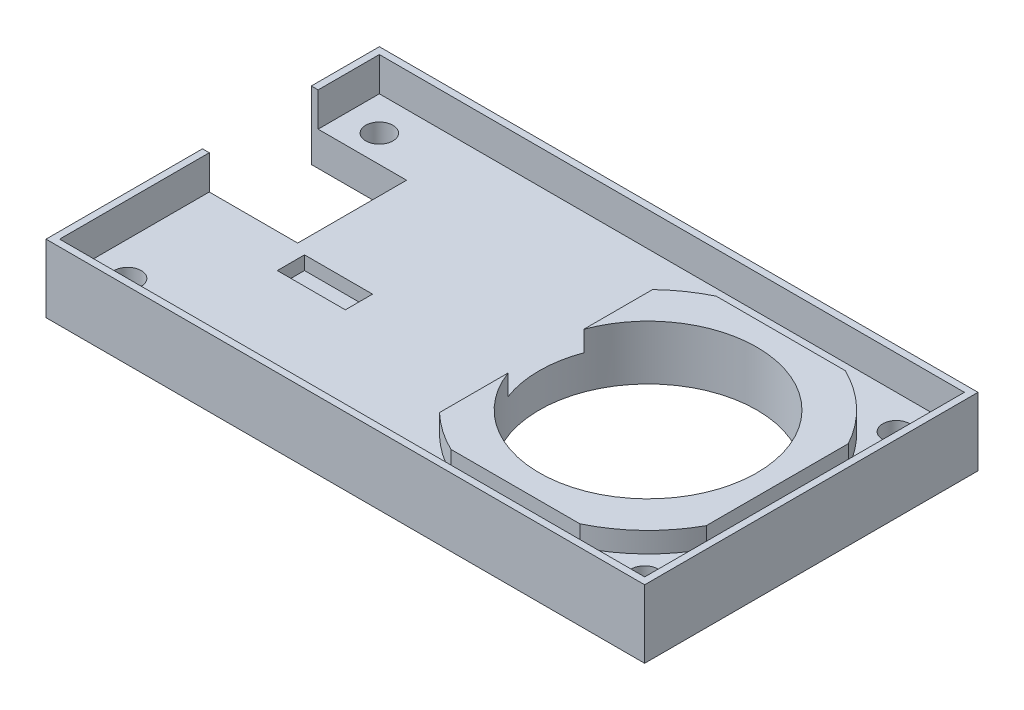
SolidWorks part; units mm, degrees
ref_plane "Front Plane" through (0, 0, 0) normal (0, 0, 1) x (1, 0, 0)
ref_plane "Top Plane" through (0, 0, 0) normal (0, 1, 0) x (1, 0, 0)
ref_plane "Right Plane" through (0, 0, 0) normal (1, 0, 0) x (0, 0, -1)
sketch "Sketch1" plane through (0, 0, 0) normal (0, 1, 0) x (1, 0, 0)
  line L1 (0, 0) -> (88, 0)
  line L2 (0, 0) -> (0, 49)
  line L3 (0, 49) -> (88, 49)
  line L4 (88, 0) -> (88, 49)
  dimension "D1" = 49
  dimension "D2" = 88
extrude "Boss-Extrude1" add sketch "Sketch1" along normal blind 5
sketch "Sketch2" plane through (0, 5, 0) normal (0, 1, 0) x (1, 0, 0)
  line L1 (0, 0) -> (88, 0)
  line L2 (0, 0) -> (0, 49)
  line L3 (0, 49) -> (88, 49)
  line L4 (88, 0) -> (88, 49)
  line L5 (1, 1) -> (87, 1)
  line L6 (1, 1) -> (1, 48)
  line L7 (1, 48) -> (87, 48)
  line L8 (87, 1) -> (87, 48)
  dimension "D1" = 1
  dimension "D2" = 1
  dimension "D3" = 1
  dimension "D4" = 1
extrude "Boss-Extrude2" add sketch "Sketch2" along normal blind 5
sketch "Sketch3" plane through (0, 0, 0) normal (0, -1, 0) x (-1, 0, 0)
  line L0 (-48, 0) -> (-48, 49)
  line L1 (0, 0) -> (-88, 0) construction
  line L2 (-88, 49) -> (0, 49) construction
  line L3 (-88, 0) -> (-88, 49) construction
  circle A0 centre (-64, 24.5) radius 16
  dimension "D1" = 32
  dimension "D4" = 24.5
  dimension "D5" = 16
  dimension "D2" = 90
  dimension "D3" = 40
extrude "Cut-Extrude1" cut sketch "Sketch3" against normal blind 5 contours A0
sketch "Sketch4" plane through (0, 0, 0) normal (0, -1, 0) x (1, 0, 0)
  line L0 (0, -49) -> (0, 0) construction
  line L1 (14, -23) -> (0, -23)
  line L2 (14, -23) -> (14, -39)
  line L3 (14, -39) -> (0, -39)
  line L4 (0, -23) -> (0, -39)
  line L5 (88, -49) -> (0, -49) construction
  point P8 (7, -23)
  dimension "D1" = 10
  dimension "D2" = 16
  dimension "D3" = 7
extrude "Cut-Extrude2" cut sketch "Sketch4" against normal up to surface (10 mm away)
sketch "Sketch5" plane through (0, 5, 0) normal (0, 1, 0) x (1, 0, 0)
  line L0 (1, 23) -> (1, 1) construction
  line L1 (26, 22) -> (16, 22)
  line L2 (26, 22) -> (26, 18)
  line L3 (26, 18) -> (16, 18)
  line L4 (16, 22) -> (16, 18)
  line L5 (1, 1) -> (87, 1) construction
  point P5 (16, 20)
  dimension "D1" = 10
  dimension "D2" = 4
  dimension "D3" = 15
  dimension "D4" = 17
extrude "Cut-Extrude3" cut sketch "Sketch5" against normal blind 2
sketch "Sketch6" plane through (0, 5, 0) normal (0, 1, 0) x (1, 0, 0)
  circle A0 centre (64, 24.5) radius 16
  circle A1 centre (64, 24.5) radius 21.6822
extrude "Boss-Extrude3" add sketch "Sketch6" along normal blind 3
sketch "Sketch7" plane through (0, 5, 0) normal (0, 1, 0) x (1, 0, 0)
  line L0 (1, 23) -> (1, 1) construction
  line L1 (39, 7.5441) -> (49, 7.5441)
  line L2 (39, 7.5441) -> (39, 43.0754)
  line L3 (39, 43.0754) -> (49, 43.0754)
  line L4 (49, 7.5441) -> (49, 43.0754)
  dimension "D1" = 10
  dimension "D2" = 38
extrude "Cut-Extrude4" cut sketch "Sketch7" along normal blind 3
sketch "Sketch8" plane through (0, 0, 0) normal (0, -1, 0) x (-1, 0, 0)
  line L0 (0, 0) -> (-88, 0) construction
  line L1 (-88, 0) -> (-88, 49) construction
  line L2 (-88, 24.5) -> (10.3062, 24.5)
  line L3 (10.3062, 24.5) -> (-38.8469, 24.5)
  line L4 (-44, 49) -> (-44, 0)
  line L5 (-88, 49) -> (0, 49) construction
  circle A0 centre (-82, 6) radius 2
  circle A1 centre (-6, 6) radius 2
  circle A2 centre (-6, 43) radius 2
  circle A3 centre (-82, 43) radius 2
  dimension "D1" = 6
  dimension "D2" = 6
  dimension "D3" = 4
extrude "Cut-Extrude5" cut sketch "Sketch8" against normal up to surface (5 mm away) contours A3 | A0 | A2 | A1 up to face at (57.9206, 5, -24.5)
sketch "Sketch9" plane through (0, 5, 0) normal (0, 1, 0) x (1, 0, 0)
  line L0 (1, 1) -> (87, 1) construction
  line L1 (87, 48) -> (46.3248, 48)
  line L2 (87, 48) -> (87, 1)
  line L3 (87, 1) -> (46.3248, 1)
  line L4 (46.3248, 48) -> (46.3248, 1)
  line L6 (83, 44) -> (48.0176, 44)
  line L7 (83, 44) -> (83, 5)
  line L8 (83, 5) -> (48.0176, 5)
  line L9 (48.0176, 44) -> (48.0176, 5)
  dimension "D1" = 4
  dimension "D2" = 4
  dimension "D3" = 4
extrude "Cut-Extrude6" cut sketch "Sketch9" along normal up to surface (3 mm away) up to face at (65.9206, 8, -24.5)
